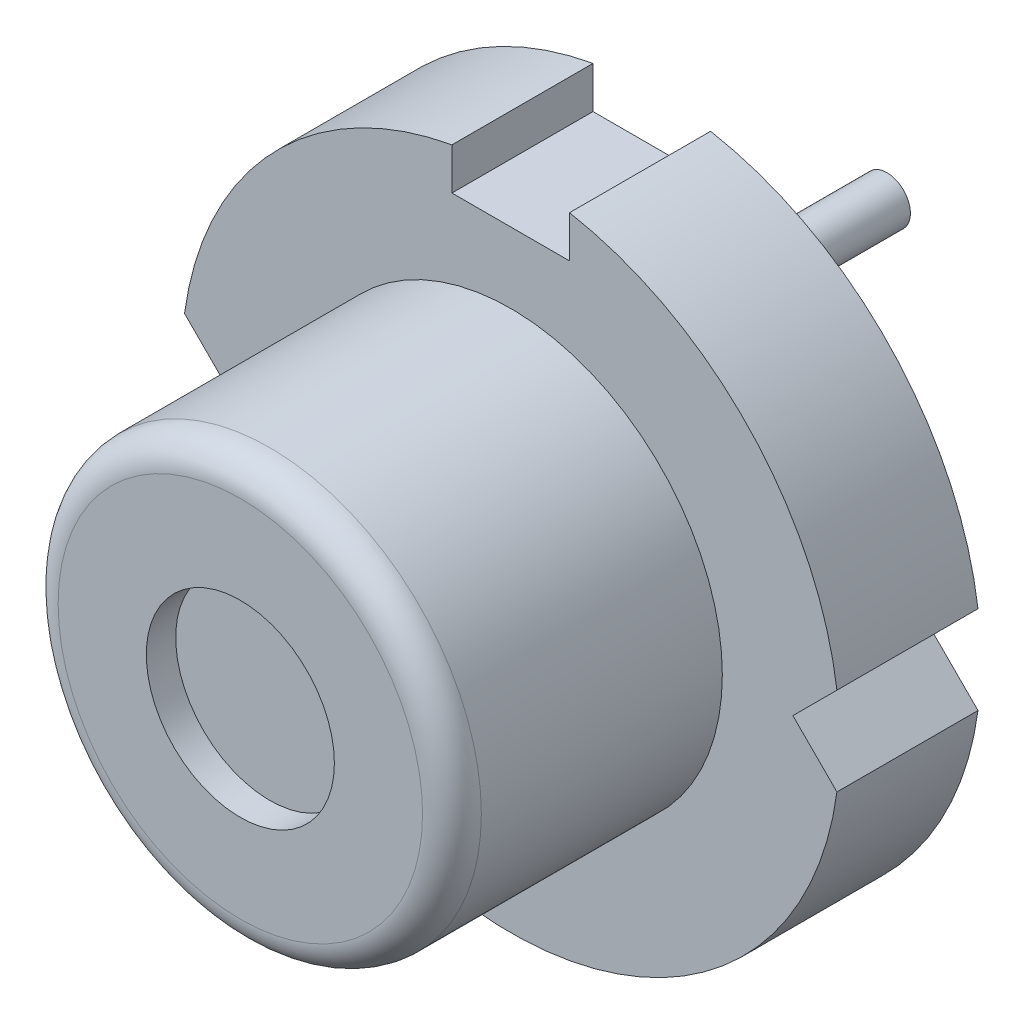
SolidWorks part; units mm, degrees
material "Brass"
ref_plane "Front Plane" through (0, 0, 0) normal (0, 0, 1) x (1, 0, 0)
ref_plane "Top Plane" through (0, 0, 0) normal (0, 1, 0) x (1, 0, 0)
ref_plane "Right Plane" through (0, 0, 0) normal (1, 0, 0) x (0, 0, -1)
sketch "Sketch1" plane through (0, 0, 0) normal (0, 1, 0) x (1, 0, 0)
  line L0 (2.8, 0) -> (0, 0)
  line L1 (0, 0) -> (0, -1.2)
  line L2 (0, -1.2) -> (2.8, -1.2)
  line L3 (2.8, -1.2) -> (2.8, 0)
  line L4 (0, 0) -> (0, -1.2) construction
revolve "Revolve1" add sketch "Sketch1" angle 360 about L4
sketch "Sketch2" plane through (0, 0, 1.2) normal (0, 0, 1) x (1, 0, 0)
  line L0 (2.7748, 0.3748) -> (2.4, 0)
  line L1 (2.4, 0) -> (2.7748, -0.3748)
  arc A0 (2.7748, -0.3748) -> (2.7748, 0.3748) centre (0, 0) ccw
extrude "Cut-Extrude1" cut sketch "Sketch2" against normal through all
sketch "Sketch3" plane through (0, 0, 1.2) normal (0, 0, 1) x (1, 0, 0)
  line L0 (-2.7748, -0.3748) -> (-2.4, 0)
  line L1 (-2.4, 0) -> (-2.7748, 0.3748)
  arc A0 (-2.7748, 0.3748) -> (-2.7748, -0.3748) centre (0, 0) ccw
extrude "Cut-Extrude2" cut sketch "Sketch3" against normal through all
sketch "Sketch4" plane through (0, 0, 1.2) normal (0, 0, 1) x (1, 0, 0)
  line L0 (-0.5, 2.755) -> (-0.5, 2.4)
  line L1 (-0.5, 2.4) -> (0.5, 2.4)
  line L2 (0.5, 2.4) -> (0.5, 2.755)
  arc A0 (0.5, 2.755) -> (-0.5, 2.755) centre (0, 0) ccw
extrude "Cut-Extrude3" cut sketch "Sketch4" against normal blind 1.2
hole_wizard "Ø0.9 (0.9) Diameter Hole1" positions "Sketch6" profile "Sketch5" hole size "Ø0.9" standard "ANSI Metric"
sketch "Sketch6" plane through (0, 0, 0) normal (0, 0, -1) x (-1, 0, 0)
  point P0 (0, 1)
sketch "Sketch5" plane through (0, 1, 0) normal (1, 0, 0) x (0, 1, 0)
  line L0 (0, 0) -> (0, 1.2)
  line L1 (0, 1.2) -> (0.45, 1.2)
  line L2 (0.45, 1.2) -> (0.45, 0)
  line L5 (0.45, 0) -> (0, 0)
  line L11 (0, -6.35) -> (0, 107.95) construction
  dimension "Thru Hole Dia." = 0.9
  dimension "Thru Hole Depth" = 1.2
hole_wizard "Ø0.9 (0.9) Diameter Hole2" positions "Sketch8" profile "Sketch7" hole size "Ø0.9" standard "ANSI Metric"
sketch "Sketch8" plane through (0, 0, 0) normal (0, 0, -1) x (-1, 0, 0)
  point P0 (0, -1)
sketch "Sketch7" plane through (0, -1, 0) normal (1, 0, 0) x (0, 1, 0)
  line L0 (0, 0) -> (0, 1.2)
  line L1 (0, 1.2) -> (0.45, 1.2)
  line L2 (0.45, 1.2) -> (0.45, 0)
  line L5 (0.45, 0) -> (0, 0)
  line L11 (0, -6.35) -> (0, 107.95) construction
  dimension "Thru Hole Dia." = 0.9
  dimension "Thru Hole Depth" = 1.2
sketch "Sketch9" plane through (0, 0, 0) normal (0, 1, 0) x (1, 0, 0)
  line L0 (1.8, -1.2) -> (0, -1.2)
  line L1 (0, -1.2) -> (0, -3.5)
  line L2 (0, -3.5) -> (1.8, -3.5)
  line L3 (1.8, -3.5) -> (1.8, -1.2)
  line L4 (0, -1.2) -> (0, -3.5) construction
revolve "Revolve2" add sketch "Sketch9" angle 360 about L4
ref_plane "Plane1" through (0, 0, 0) normal (0, -1, 0) x (1, 0, 0)
sketch "Sketch10" plane through (0, 0, 0) normal (0, -1, 0) x (1, 0, 0)
  line L0 (-0.8, 0) -> (-1, 0)
  line L1 (-1, 0) -> (-1, -2)
  line L2 (-1, -2) -> (-0.8, -2)
  line L3 (-0.8, -2) -> (-0.8, 0)
  line L4 (-1, 0) -> (-1, -2) construction
revolve "Revolve3" add sketch "Sketch10" angle 360 about L4
ref_plane "Plane2" through (0, -1, 0) normal (0, -1, 0) x (1, 0, 0)
sketch "Sketch11" plane through (0, -1, 0) normal (0, -1, 0) x (1, 0, 0)
  line L0 (0.2, 0.25) -> (0, 0.25)
  line L1 (0, 0.25) -> (0, -2)
  line L2 (0, -2) -> (0.2, -2)
  line L3 (0.2, -2) -> (0.2, 0.25)
  line L4 (0, 0.25) -> (0, -2) construction
revolve "Revolve4" add sketch "Sketch11" angle 360 about L4
ref_plane "Plane3" through (0, 1, 0) normal (0, -1, 0) x (1, 0, 0)
sketch "Sketch12" plane through (0, 1, 0) normal (0, -1, 0) x (1, 0, 0)
  line L0 (0.2, 0.25) -> (0, 0.25)
  line L1 (0, 0.25) -> (0, -2)
  line L2 (0, -2) -> (0.2, -2)
  line L3 (0.2, -2) -> (0.2, 0.25)
  line L4 (0, 0.25) -> (0, -2) construction
revolve "Revolve5" add sketch "Sketch12" angle 360 about L4
hole_wizard "Ø1.6 (1.6) Diameter Hole1" positions "Sketch14" profile "Sketch13" hole size "Ø1.6" standard "ANSI Metric"
sketch "Sketch14" plane through (0, 0, 3.5) normal (0, 0, 1) x (1, 0, 0)
  point P0 (0, 0)
sketch "Sketch13" plane through (0, 0, 3.5) normal (1, 0, 0) x (0, -1, 0)
  line L0 (0, 0) -> (0, 0.25)
  line L1 (0, 0.25) -> (0.8, 0.25)
  line L2 (0.8, 0.25) -> (0.8, 0)
  line L5 (0.8, 0) -> (0, 0)
  line L10 (0, 0.25) -> (-0.8, 0.25) construction
  line L11 (0, -6.35) -> (0, 107.95) construction
  dimension "Hole Dia." = 1.6
  dimension "Hole Depth" = 0.25
  dimension "Drill Angle" = 180
fillet "Fillet1" radius 0.25 1 edges at (1.8, 0, 3.5)
